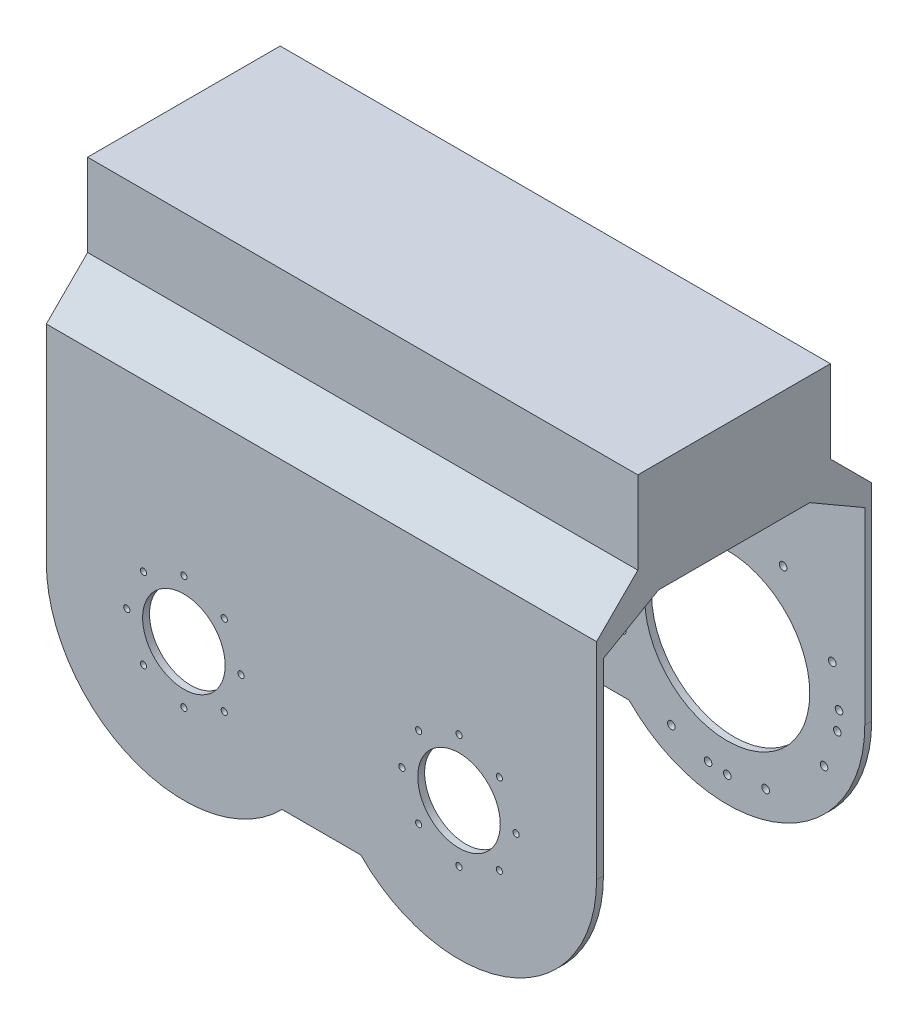
SolidWorks part; units mm, degrees
ref_plane "前视基准面" through (0, 0, 0) normal (0, 0, 1) x (1, 0, 0)
ref_plane "上视基准面" through (0, 0, 0) normal (0, 1, 0) x (1, 0, 0)
ref_plane "右视基准面" through (0, 0, 0) normal (1, 0, 0) x (0, 0, -1)
other "Configuration Table"
sketch "草图1" plane through (0, 0, 0) normal (0, 0, 1) x (1, 0, 0)
  line L0 (0, 350.9244) -> (0, -92.7876) construction
  line L1 (-181.3077, 0) -> (720.1521, 0) construction
  line L5 (200, 180) -> (200, 0)
  line L6 (-200, 180) -> (-200, 0)
  line L8 (-200, 180) -> (-200, 240)
  line L9 (-200, 240) -> (200, 240)
  line L10 (200, 240) -> (200, 180)
  line L11 (-28.5857, -70) -> (28.5857, -70)
  circle A0 centre (100, 0) radius 60
  circle A1 centre (100, 0) radius 85 construction
  arc A2 (28.5857, -70) -> (200, 0) centre (100, 0) ccw
  circle A3 centre (-100, 0) radius 85 construction
  circle A4 centre (-100, 0) radius 60
  arc A5 (-28.5857, -70) -> (-200, 0) centre (-100, 0) cw
  point P16 (0, 176.5389)
  point P17 (0, 80)
  dimension "D1" = 120
  dimension "D2" = 170
  dimension "D4" = 200
  dimension "D3" = 100
  dimension "D5" = 70
  dimension "D8" = 180
  dimension "D9" = 400
  dimension "D10" = 240
extrude "凸台-拉伸1" add sketch "草图1" along normal blind 200
sketch "草图2" plane through (0, 0, 0) normal (1, 0, 0) x (0, 0, -1)
  line L0 (-100, 291.5151) -> (-100, -211.064) construction
  line L1 (0, 0) -> (0, 240) construction
  line L2 (-200, 0) -> (-200, 240) construction
  line L5 (-195, 136.906) -> (-195, -163.094)
  line L6 (-195, -163.094) -> (-5, -163.094)
  line L7 (-5, 136.906) -> (-5, -163.094)
  line L8 (0, -100) -> (0, 0) construction
  line L10 (-195, 136.906) -> (-155, 160)
  line L11 (-155, 160) -> (-45, 160)
  line L12 (-5, 136.906) -> (-45, 160)
  line L13 (-200, 240) -> (0, 240) construction
  point P15 (-100, 160)
  dimension "D1" = 5
  dimension "D2" = 80
  dimension "D3" = 300
  dimension "D4" = 30
  dimension "D5" = 110
extrude "切除-拉伸1" cut sketch "草图2" against normal through all both and the other way through all
sketch "草图3" plane through (0, 0, 0) normal (1, 0, 0) x (0, 0, -1)
  line L0 (-100, 274.1056) -> (-100, -160.0053) construction
  line L1 (0, 0) -> (0, 240) construction
  line L2 (-200, 0) -> (-200, 240) construction
  line L3 (-170, 240) -> (-170, 180)
  line L4 (-200, 240) -> (0, 240) construction
  line L6 (-170, 180) -> (-200, 150)
  line L7 (-200, 0) -> (-200, 240) construction
  line L8 (-200, 150) -> (-200, 240)
  line L9 (-200, 240) -> (-170, 240)
  line L10 (0, 240) -> (-30, 240)
  line L11 (0, 150) -> (0, 240)
  line L12 (-30, 180) -> (0, 150)
  line L13 (-30, 240) -> (-30, 180)
  point P21 (-170, 180)
  dimension "D1" = 90
  dimension "D2" = 140
  dimension "D3" = 45
extrude "切除-拉伸2" cut sketch "草图3" against normal through all both and the other way through all
sketch "草图4" plane through (0, 0, 0) normal (0, 0, -1) x (-1, 0, 0)
  line L0 (0, 284.6971) -> (0, -204.9481) construction
  line L1 (-100, 0) -> (-72.051, 76.2917) construction
  line L2 (-100, 0) -> (-100, 81.25) construction
  line L3 (-100, 0) -> (-113.9413, 80.045) construction
  line L4 (-100, 0) -> (-140.625, 70.3646) construction
  line L5 (100, 0) -> (140.625, 70.3646) construction
  line L6 (100, 0) -> (113.9413, 80.045) construction
  line L7 (100, 0) -> (100, 81.25) construction
  line L8 (100, 0) -> (72.051, 76.2917) construction
  circle A0 centre (-100, 0) radius 81.25 construction
  circle A1 centre (-72.051, 76.2917) radius 2.75
  circle A2 centre (-100, 81.25) radius 2.75
  circle A3 centre (-113.9413, 80.045) radius 2.75
  circle A4 centre (-140.625, 70.3646) radius 2.75
  circle A5 centre (-23.7083, -27.949) radius 2.75
  circle A6 centre (-18.75, 0) radius 2.75
  circle A7 centre (-19.955, 13.9413) radius 2.75
  circle A8 centre (-29.6354, 40.625) radius 2.75
  circle A9 centre (-127.949, -76.2917) radius 2.75
  circle A10 centre (-100, -81.25) radius 2.75
  circle A11 centre (-86.0587, -80.045) radius 2.75
  circle A12 centre (-59.375, -70.3646) radius 2.75
  circle A13 centre (-176.2917, 27.949) radius 2.75
  circle A14 centre (-181.25, 0) radius 2.75
  circle A15 centre (-180.045, -13.9413) radius 2.75
  circle A16 centre (-170.3646, -40.625) radius 2.75
  circle A17 centre (100, 0) radius 81.25 construction
  circle A18 centre (170.3646, -40.625) radius 2.75
  circle A19 centre (180.045, -13.9413) radius 2.75
  circle A20 centre (181.25, 0) radius 2.75
  circle A21 centre (176.2917, 27.949) radius 2.75
  circle A22 centre (59.375, -70.3646) radius 2.75
  circle A23 centre (86.0587, -80.045) radius 2.75
  circle A24 centre (100, -81.25) radius 2.75
  circle A25 centre (127.949, -76.2917) radius 2.75
  circle A26 centre (29.6354, 40.625) radius 2.75
  circle A27 centre (19.955, 13.9413) radius 2.75
  circle A28 centre (18.75, 0) radius 2.75
  circle A29 centre (23.7083, -27.949) radius 2.75
  circle A30 centre (140.625, 70.3646) radius 2.75
  circle A31 centre (113.9413, 80.045) radius 2.75
  circle A32 centre (100, 81.25) radius 2.75
  circle A33 centre (72.051, 76.2917) radius 2.75
  point P14 (-200, 0)
  point P41 (-100, 0)
  point P74 (100, 0)
  dimension "D1" = 162.5
  dimension "D5" = 5.5
  dimension "D2" = 30
  dimension "D3" = 30
  dimension "D4" = 9.88
  dimension "D6" = 4
extrude "切除-拉伸3" cut sketch "草图4" against normal blind 32.5
sketch "草图5" plane through (0, 0, 200) normal (0, 0, 1) x (1, 0, 0)
  circle A0 centre (-100, 0) radius 60 construction
  circle A1 centre (100, 0) radius 60 construction
  circle A2 centre (-100, 0) radius 60
  circle A3 centre (100, 0) radius 60
  circle A4 centre (100, 0) radius 30
  circle A5 centre (-100, 0) radius 30
  dimension "D1" = 60
extrude "凸台-拉伸2" add sketch "草图5" against normal up to surface (5 mm away) up to face at (100, -60, 195)
sketch "草图6" plane through (0, 0, 200) normal (0, 0, 1) x (1, 0, 0)
  line L0 (0, 0) -> (0, 283.4074) construction
  line L1 (100, 0) -> (100, 76.6247) construction
  line L2 (-100, 0) -> (-100, 76.6247) construction
  circle A0 centre (100, 0) radius 41.5 construction
  circle A1 centre (100, 41.5) radius 2.25
  circle A2 centre (129.3449, 29.3449) radius 2.25
  circle A3 centre (141.5, 0) radius 2.25
  circle A4 centre (129.3449, -29.3449) radius 2.25
  circle A5 centre (100, -41.5) radius 2.25
  circle A6 centre (70.6551, -29.3449) radius 2.25
  circle A7 centre (58.5, 0) radius 2.25
  circle A8 centre (70.6551, 29.3449) radius 2.25
  circle A9 centre (-100, 0) radius 41.5 construction
  circle A10 centre (-70.6551, 29.3449) radius 2.25
  circle A11 centre (-58.5, 0) radius 2.25
  circle A12 centre (-70.6551, -29.3449) radius 2.25
  circle A13 centre (-100, -41.5) radius 2.25
  circle A14 centre (-129.3449, -29.3449) radius 2.25
  circle A15 centre (-141.5, 0) radius 2.25
  circle A16 centre (-129.3449, 29.3449) radius 2.25
  circle A17 centre (-100, 41.5) radius 2.25
  point P9 (200, 0)
  point P26 (100, 0)
  point P44 (-100, 0)
  dimension "D1" = 83
  dimension "D2" = 4.5
  dimension "D3" = 8
extrude "切除-拉伸4" cut sketch "草图6" against normal up to surface (5 mm away) up to face at (0, 3.1093, 195)
